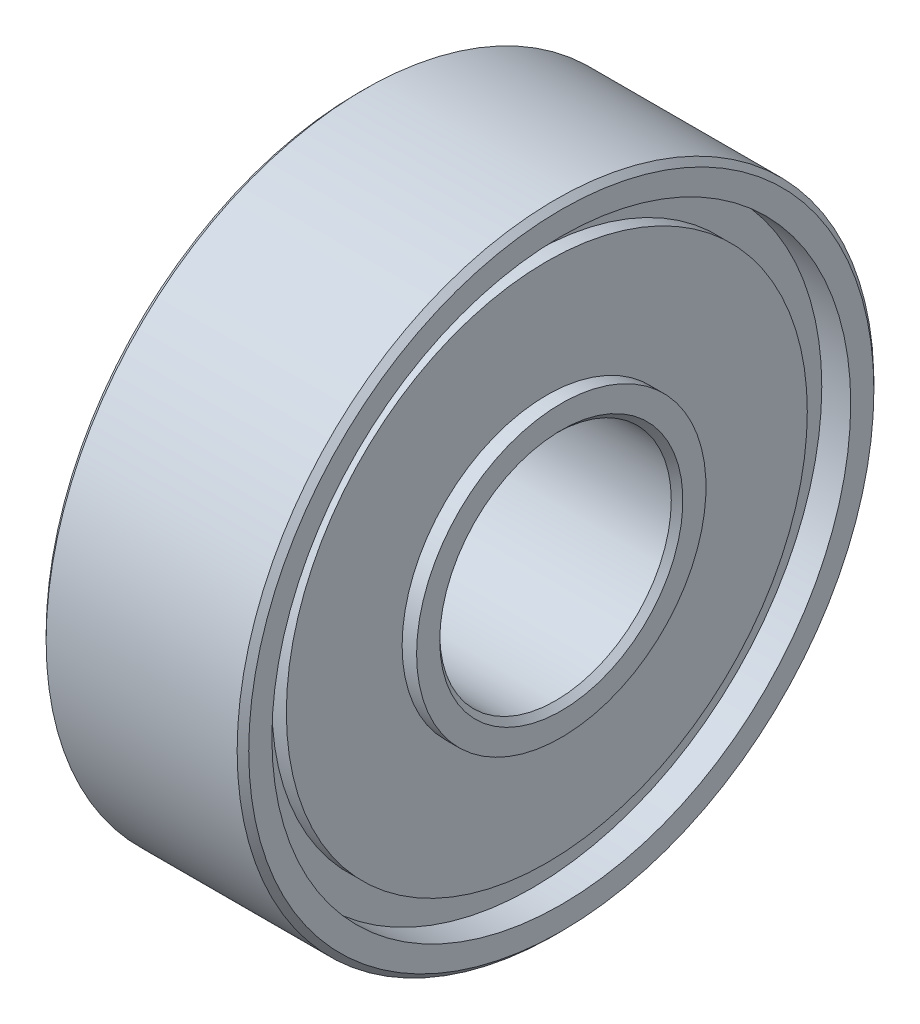
SolidWorks part; units mm, degrees
ref_plane "前视基准面" through (0, 0, 0) normal (0, 0, 1) x (1, 0, 0)
ref_plane "上视基准面" through (0, 0, 0) normal (0, 1, 0) x (1, 0, 0)
ref_plane "右视基准面" through (0, 0, 0) normal (1, 0, 0) x (0, 0, -1)
sketch "草图1" plane through (0, 0, 0) normal (0, 0, 1) x (1, 0, 0)
  line L0 (-6.477, 0) -> (6.3562, 0) construction
  line L1 (0, 7.5766) -> (0, -9.0509) construction
  line L2 (-3.5, 4) -> (3.5, 4)
  line L3 (3.5, 4) -> (3.5, 5)
  line L4 (3.5, 5) -> (3, 5)
  line L5 (3, 5) -> (3, 9)
  line L6 (3, 9) -> (2.5, 9)
  line L7 (2.5, 9) -> (2.5, 10)
  line L8 (2.5, 10) -> (3.5, 10)
  line L9 (3.5, 10) -> (3.5, 11)
  line L10 (3.5, 11) -> (-3.5, 11)
  line L11 (-3.5, 10) -> (-3.5, 11)
  line L12 (-2.5, 10) -> (-3.5, 10)
  line L13 (-2.5, 9) -> (-2.5, 10)
  line L14 (-3, 9) -> (-2.5, 9)
  line L15 (-3, 5) -> (-3, 9)
  line L16 (-3.5, 5) -> (-3, 5)
  line L17 (-3.5, 4) -> (-3.5, 5)
  point P16 (0, 11)
  point P23 (0, 4)
  dimension "D1" = 4
  dimension "D2" = 7
  dimension "D3" = 1
  dimension "D4" = 11
  dimension "D5" = 1
  dimension "D6" = 1
  dimension "D7" = 0.5
  dimension "D8" = 0.5
revolve "旋转1" add sketch "草图1" angle 360 about L0
chamfer "倒角1" distance 0.2 angle 45 4 edges at (-3.5, 0, 4) (3.5, 0, 4) (3.5, 0, 11) (-3.5, 0, 11)
